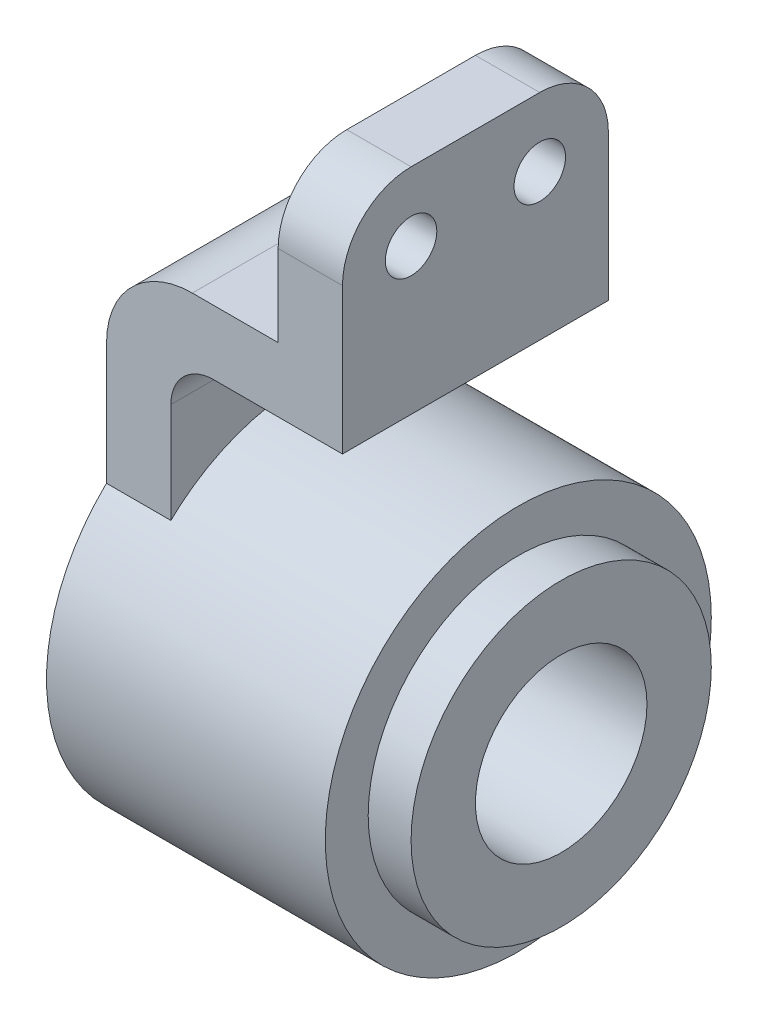
SolidWorks part; units mm, degrees
ref_plane "Front Plane" through (0, 0, 0) normal (0, 0, 1) x (1, 0, 0)
ref_plane "Top Plane" through (0, 0, 0) normal (0, 1, 0) x (1, 0, 0)
ref_plane "Right Plane" through (0, 0, 0) normal (1, 0, 0) x (0, 0, -1)
sketch "Sketch1" plane through (0, 0, 0) normal (0, 0, 1) x (1, 0, 0)
  line L0 (0, 0) -> (0, 45)
  line L1 (0, 45) -> (65, 45)
  line L2 (65, 45) -> (65, 35)
  line L3 (65, 35) -> (75, 35)
  line L4 (75, 35) -> (75, 0)
  line L5 (75, 0) -> (0, 0)
  dimension "D1" = 75
  dimension "D2" = 10
  dimension "D3" = 45
  dimension "D4" = 35
revolve "Revolve1" add sketch "Sketch1" angle 360 about L5
sketch "Sketch4" plane through (0, 0, 0) normal (0, 0, 1) x (1, 0, 0)
  line L0 (0, 0) -> (0, 81)
  line L1 (0, 81) -> (40, 81)
  line L2 (40, 81) -> (40, 116)
  line L3 (40, 116) -> (55, 116)
  line L4 (55, 116) -> (55, 66)
  line L5 (55, 66) -> (15, 66)
  line L6 (15, 66) -> (15, 0)
  line L9 (15, 0) -> (0, 0)
  dimension "D1" = 15
  dimension "D2" = 15
  dimension "D3" = 15
  dimension "D4" = 55
  dimension "D5" = 116
  dimension "D6" = 50
extrude "Boss-Extrude1" add sketch "Sketch4" along normal mid plane 62 separate body
hole_wizard "Hole2" positions "Sketch6" profile "Sketch7" legacy end condition up to next
sketch "Sketch6" plane through (0, 0, 0) normal (-1, 0, 0) x (0, 0, 1)
  point P0 (0, 0)
sketch "Sketch7" plane through (0, 0, 0) normal (0, 1, 0) x (0, 0, 1)
  line L0 (0, 0) -> (0, 75)
  line L1 (0, 75) -> (20, 75)
  line L2 (20, 75) -> (20, 0)
  line L3 (20, 0) -> (0, 0)
  line L4 (0, 110) -> (0, -10) construction
  dimension "Diameter" = 40
  dimension "Depth" = 75
hole_wizard "Hole3" positions "Sketch8" profile "Sketch9" legacy end condition through all
sketch "Sketch8" plane through (75, 0, 0) normal (1, 0, 0) x (0, 0, -1)
  point P0 (0, 0)
sketch "Sketch9" plane through (75, 0, 0) normal (0, 1, 0) x (0, 0, -1)
  line L0 (0, 0) -> (0, 75)
  line L1 (0, 75) -> (20, 75)
  line L2 (20, 75) -> (20, 0)
  line L3 (20, 0) -> (0, 0)
  line L4 (0, 110) -> (0, -10) construction
  dimension "Diameter" = 40
  dimension "Depth" = 75
fillet "Fillet1" radius 10 1 edges at (15, 66, 0)
fillet "Fillet2" radius 20 1 edges at (0, 81, 0)
fillet "Fillet3" radius 16 2 edges at (47.5, 116, -31) (47.5, 116, 31)
hole_wizard "Hole4" positions "Sketch10" profile "Sketch11" legacy end condition through all
sketch "Sketch10" plane through (55, 0, 0) normal (1, 0, 0) x (0, 0, -1)
  point P0 (15, 100)
  point P3 (-15, 100)
sketch "Sketch11" plane through (55, 100, -15) normal (0, 1, 0) x (0, 0, -1)
  line L0 (0, 0) -> (0, 55)
  line L1 (0, 55) -> (6, 55)
  line L2 (6, 55) -> (6, 0)
  line L3 (6, 0) -> (0, 0)
  line L4 (0, 110) -> (0, -10) construction
  dimension "Diameter" = 12
  dimension "Depth" = 55
